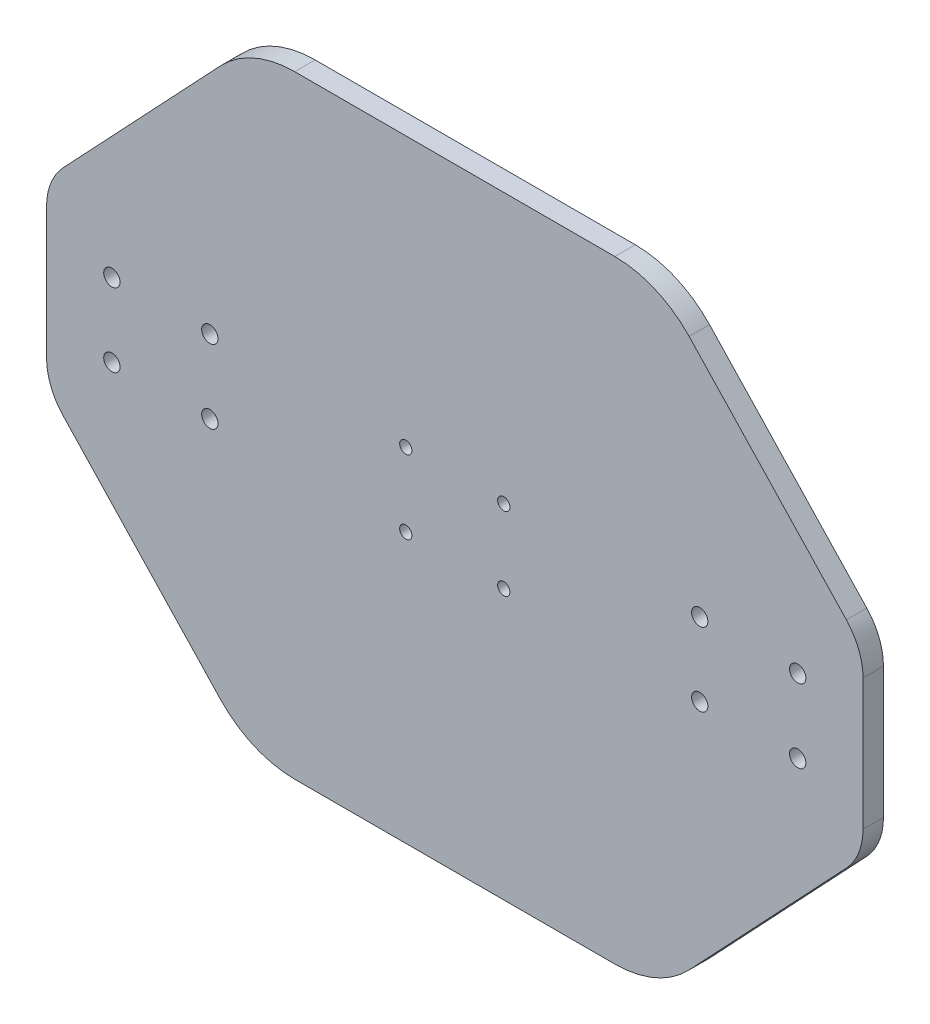
SolidWorks part; units mm, degrees
ref_plane "Alzado" through (0, 0, 0) normal (0, 0, 1) x (1, 0, 0)
ref_plane "Planta" through (0, 0, 0) normal (0, 1, 0) x (1, 0, 0)
ref_plane "Vista lateral" through (0, 0, 0) normal (1, 0, 0) x (0, 0, -1)
sketch "Croquis1" plane through (0, 0, 0) normal (0, 0, 1) x (1, 0, 0)
  line L0 (200, 5.6488) -> (0, 5.6488) construction
  line L1 (200, -69.4012) -> (0, -69.4012)
  line L2 (200, -69.4012) -> (200, 80.6988)
  line L3 (200, 80.6988) -> (0, 80.6988)
  line L4 (0, -69.4012) -> (0, 80.6988)
  line L5 (100, 80.6988) -> (100, -69.4012) construction
  line L6 (70, 80.6988) -> (70, 49.6988) construction
  line L7 (70, 49.6988) -> (130, 49.6988) construction
  line L8 (130, 49.6988) -> (130, 80.6988) construction
  circle A0 centre (150, 45.6988) radius 12 construction
  circle A1 centre (50, 45.6988) radius 12 construction
  circle A4 centre (50, 45.6988) radius 2.5 construction
  circle A5 centre (150, 45.6988) radius 2.5 construction
  circle A6 centre (150, -34.4012) radius 2.5 construction
  circle A7 centre (150, -34.4012) radius 12 construction
  circle A10 centre (50, -34.4012) radius 2.5 construction
  circle A11 centre (50, -34.4012) radius 12 construction
  point P14 (100, 49.6988)
  dimension "D9" = 5
  dimension "D10" = 5
  dimension "D1" = 31
  dimension "D2" = 60
  dimension "D3" = 40.05
  dimension "D4" = 20
extrude "Saliente-Extruir1" add sketch "Croquis1" along normal blind 5
sketch "Croquis2" plane through (0, 0, 5) normal (0, 0, 1) x (1, 0, 0)
  line L0 (200, 5.6488) -> (0, 5.6488) construction
  line L1 (200, -69.4012) -> (200, 80.6988) construction
  line L2 (0, 80.6988) -> (0, -69.4012) construction
  line L3 (100, 80.6988) -> (100, -69.4012) construction
  line L4 (200, 80.6988) -> (0, 80.6988) construction
  line L5 (0, -69.4012) -> (200, -69.4012) construction
  line L6 (28, -3.3512) -> (28, 14.6488) construction
  line L7 (88, -3.3512) -> (112, -3.3512) construction
  line L8 (88, -3.3512) -> (88, 14.6488) construction
  line L9 (88, 14.6488) -> (112, 14.6488) construction
  line L10 (112, -3.3512) -> (112, 14.6488) construction
  line L11 (88, -3.3512) -> (112, 14.6488) construction
  line L12 (88, 14.6488) -> (112, -3.3512) construction
  line L13 (16, -3.3512) -> (40, -3.3512) construction
  line L14 (16, -3.3512) -> (16, 14.6488) construction
  line L15 (16, 14.6488) -> (40, 14.6488) construction
  line L16 (40, -3.3512) -> (40, 14.6488) construction
  line L17 (16, -3.3512) -> (40, 14.6488) construction
  line L18 (16, 14.6488) -> (40, -3.3512) construction
  circle A0 centre (88, 14.6488) radius 1.5
  circle A1 centre (112, 14.6488) radius 1.5
  circle A2 centre (88, -3.3512) radius 1.5
  circle A3 centre (112, -3.3512) radius 1.5
  circle A4 centre (16, 14.6488) radius 2
  circle A5 centre (40, 14.6488) radius 2
  circle A6 centre (40, -3.3512) radius 2
  circle A7 centre (16, -3.3512) radius 2
  circle A8 centre (184, -3.3512) radius 2
  circle A9 centre (160, -3.3512) radius 2
  circle A10 centre (160, 14.6488) radius 2
  circle A11 centre (184, 14.6488) radius 2
  point P12 (100, 5.6488)
  point P22 (28, 5.6488)
  dimension "D3" = 3
  dimension "D7" = 4
  dimension "D1" = 24
  dimension "D2" = 18
  dimension "D4" = 24
  dimension "D5" = 18
  dimension "D6" = 72
extrude "Cortar-Extruir1" cut sketch "Croquis2" against normal blind 10
sketch "Croquis3" plane through (0, 0, 0) normal (0, 0, -1) x (-1, 0, 0)
  line L0 (-200, 5.6488) -> (0, 5.6488) construction
  line L1 (-200, -69.4012) -> (-200, 80.6988) construction
  line L2 (0, 80.6988) -> (0, -69.4012) construction
  line L3 (-100, 80.6988) -> (-100, -69.4012) construction
  line L4 (-200, 80.6988) -> (0, 80.6988) construction
  line L5 (0, -69.4012) -> (-200, -69.4012) construction
  line L6 (-157.4016, 72.8458) -> (-195.9157, 31.9822)
  line L11 (-200, -69.4012) -> (0, 80.6988) construction
  line L12 (-200, 80.6988) -> (0, -69.4012) construction
  line L13 (-42.5984, 72.8458) -> (-4.0843, 31.9822)
  line L14 (-42.5984, -61.5481) -> (-4.0843, -20.6845)
  line L15 (-157.4016, -61.5481) -> (-195.9157, -20.6845)
  line L16 (-60.7914, 80.6988) -> (0, 80.6988)
  line L17 (-200, 80.6988) -> (-139.2086, 80.6988)
  line L18 (-200, 80.6988) -> (-200, 21.6941)
  line L19 (-200, -69.4012) -> (0, -69.4012)
  line L20 (-139.2086, -69.4012) -> (-60.7914, -69.4012) construction
  line L24 (0, 80.6988) -> (0, 21.6941)
  line L25 (-200, 80.6988) -> (0, -69.4012) construction
  line L26 (-200, -69.4012) -> (0, 80.6988) construction
  line L27 (-200, -10.3964) -> (-200, -69.4012)
  line L28 (0, -10.3964) -> (0, -69.4012)
  line L29 (-200, 21.6941) -> (-200, -10.3964) construction
  line L30 (-139.2086, 80.6988) -> (-60.7914, 80.6988) construction
  line L31 (0, 21.6941) -> (0, -10.3964) construction
  line L32 (-139.2086, -69.4012) -> (-60.7914, -69.4012) construction
  arc A0 (-195.9157, 31.9822) -> (-200, 21.6941) centre (-185, 21.6941) ccw
  arc A1 (-4.0843, 31.9822) -> (0, 21.6941) centre (-15, 21.6941) cw
  arc A2 (-4.0843, -20.6845) -> (0, -10.3964) centre (-15, -10.3964) ccw
  arc A3 (-195.9157, -20.6845) -> (-200, -10.3964) centre (-185, -10.3964) cw
  arc A4 (-42.5984, -61.5481) -> (-60.7914, -69.4012) centre (-60.7914, -44.4012) cw
  arc A5 (-157.4016, -61.5481) -> (-139.2086, -69.4012) centre (-139.2086, -44.4012) ccw
  arc A6 (-42.5984, 72.8458) -> (-60.7914, 80.6988) centre (-60.7914, 55.6988) ccw
  arc A7 (-157.4016, 72.8458) -> (-139.2086, 80.6988) centre (-139.2086, 55.6988) cw
  point P12 (-100, 5.6488)
  point P18 (-100, 5.6488)
  line M28 (-200, 80.6988) -> (-200, -69.4012)
  line M29 (-200, -69.4012) -> (0, -69.4012)
  line M30 (0, -69.4012) -> (0, 80.6988)
  line M31 (0, 80.6988) -> (-200, 80.6988)
  dimension "D3" = 15
  dimension "D4" = 25
extrude "Cortar-Extruir2" cut sketch "Croquis3" against normal blind 400 contours L6 A7 A0 M31 M28 | A6 L13 A1 M30 M31 | L14 A4 L19 A2 M30 | A5 L15 A3 M28 M29
